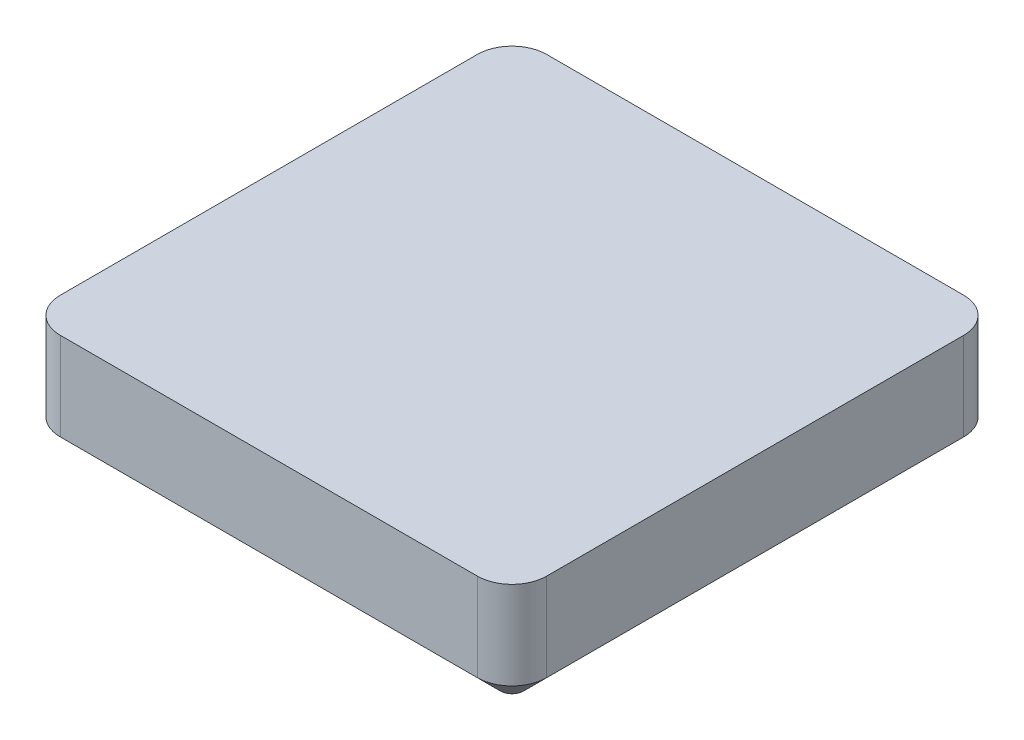
SolidWorks part; units mm, degrees
ref_plane "前视基准面" through (0, 0, 0) normal (0, 0, 1) x (1, 0, 0)
ref_plane "上视基准面" through (0, 0, 0) normal (0, 1, 0) x (1, 0, 0)
ref_plane "右视基准面" through (0, 0, 0) normal (1, 0, 0) x (0, 0, -1)
sketch "草图1" plane through (0, 0, 0) normal (0, 1, 0) x (1, 0, 0)
  line L1 (0, 0) -> (210, 0)
  line L2 (0, 0) -> (0, -210)
  line L3 (0, -210) -> (210, -210)
  line L4 (210, 0) -> (210, -210)
extrude "凸台-拉伸1" add sketch "草图1" along normal blind 48
fillet "圆角1" radius 15 4 edges at (0, 24, 0) (210, 24, 0) (210, 24, 210) (0, 24, 210)
chamfer "倒角1" distance 10 angle 45 8 edges at (210, 0, 105) (205.6066, 0, 4.3934) (205.6066, 0, 205.6066) (105, 0, 0) (105, 0, 210) (4.3934, 0, 4.3934) (4.3934, 0, 205.6066) (0, 0, 105)
